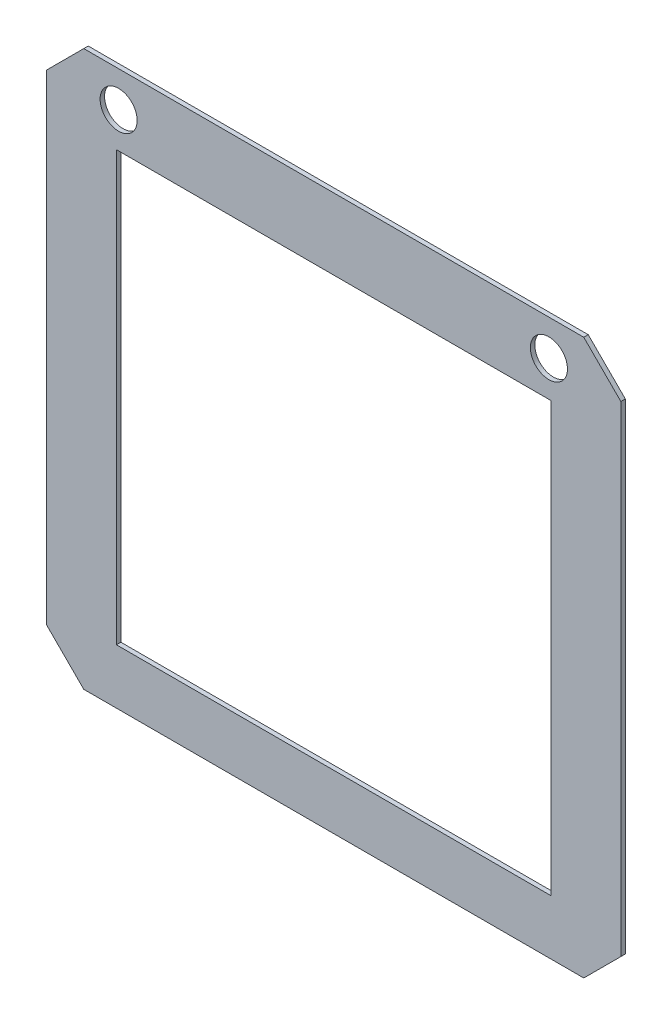
SolidWorks part; units mm, degrees
ref_plane "Plan de face" through (0, 0, 0) normal (0, 0, 1) x (1, 0, 0)
ref_plane "Plan de dessus" through (0, 0, 0) normal (0, 1, 0) x (1, 0, 0)
ref_plane "Plan de droite" through (0, 0, 0) normal (1, 0, 0) x (0, 0, -1)
sketch "Esquisse1" plane through (0, 0, 0) normal (0, 0, 1) x (1, 0, 0)
  line L0 (-146.5, 139) -> (146.5, 139)
  line L1 (-193.5, -187) -> (193.5, -187)
  line L2 (-193.5, -187) -> (-193.5, 187)
  line L3 (-193.5, 187) -> (193.5, 187)
  line L4 (193.5, -187) -> (193.5, 187)
  line L5 (-193.5, -187) -> (193.5, 187) construction
  line L6 (-193.5, 187) -> (193.5, -187) construction
  line L7 (146.5, 139) -> (146.5, -150)
  line L8 (146.5, -150) -> (-146.5, -150)
  line L9 (-146.5, -150) -> (-146.5, 139)
  point P0 (0, 0)
  dimension "D1" = 374
  dimension "D2" = 387
  dimension "D3" = 48
  dimension "D4" = 37
  dimension "D5" = 47
  dimension "D6" = 47
extrude "Boss.-Extru.1" add sketch "Esquisse1" along normal blind 3
chamfer "Chanfrein1" distance 25 angle 45 4 edges at (-193.5, -187, 1.5) (193.5, -187, 1.5) (193.5, 187, 1.5) (-193.5, 187, 1.5)
sketch "Esquisse2" plane through (0, 0, 3) normal (0, 0, 1) x (1, 0, 0)
  line L0 (0, 187) -> (0, 163) construction
  line L1 (168.5, 187) -> (-168.5, 187) construction
  line L2 (0, 163) -> (145, 163) construction
  line L3 (0, 163) -> (-145, 163) construction
  circle A1 centre (145, 163) radius 12.5
  circle A2 centre (-145, 163) radius 12.5
  dimension "D1" = 25
  dimension "D2" = 25
  dimension "D3" = 24
  dimension "D4" = 145
  dimension "D5" = 145
extrude "Enlèv. mat.-Extru.1" cut sketch "Esquisse2" against normal blind 3
